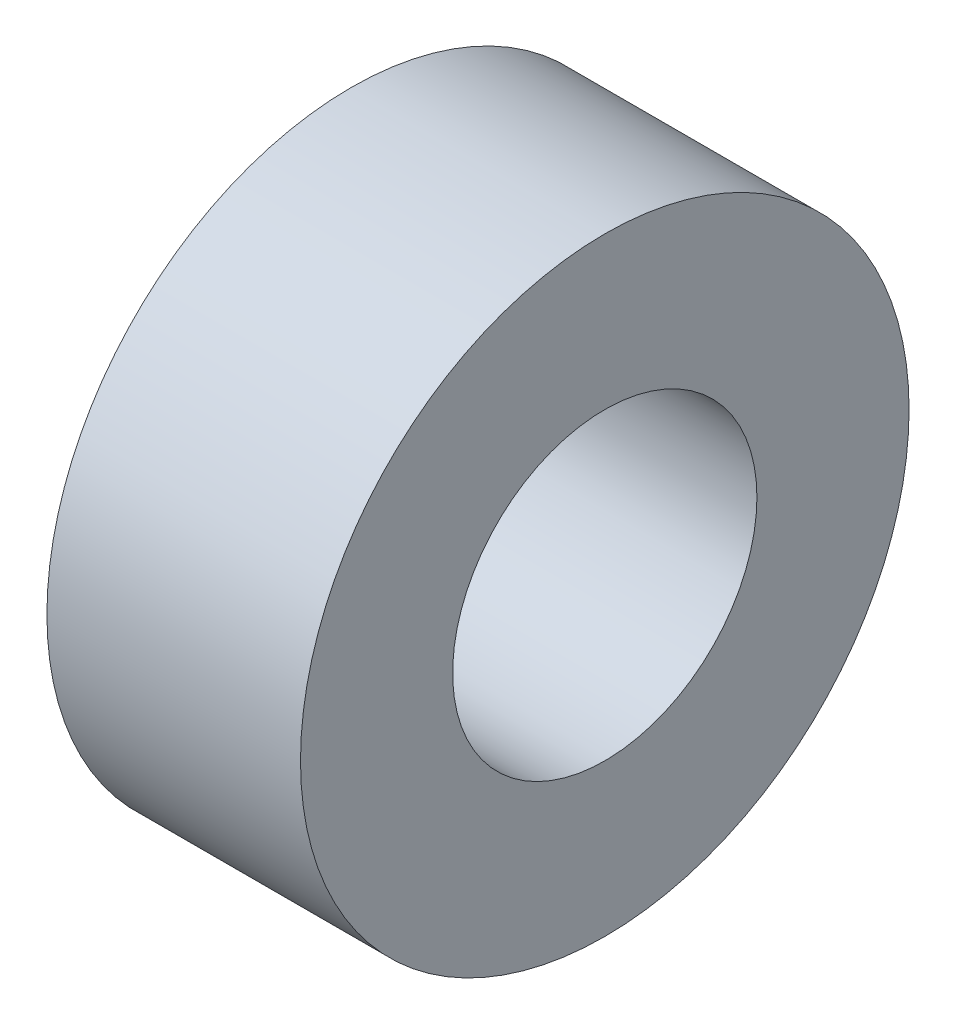
SolidWorks part; units mm, degrees
ref_plane "Front Plane" through (0, 0, 0) normal (0, 0, 1) x (1, 0, 0)
ref_plane "Top Plane" through (0, 0, 0) normal (0, 1, 0) x (1, 0, 0)
ref_plane "Right Plane" through (0, 0, 0) normal (1, 0, 0) x (0, 0, -1)
sketch "Sketch1" plane through (0, 0, 0) normal (1, 0, 0) x (0, 0, -1)
  circle A0 centre (0, 0) radius 1.5
  circle A1 centre (0, 0) radius 3
  dimension "D1" = 3
  dimension "D2" = 6
extrude "Boss-Extrude1" add sketch "Sketch1" along normal blind 2.5
